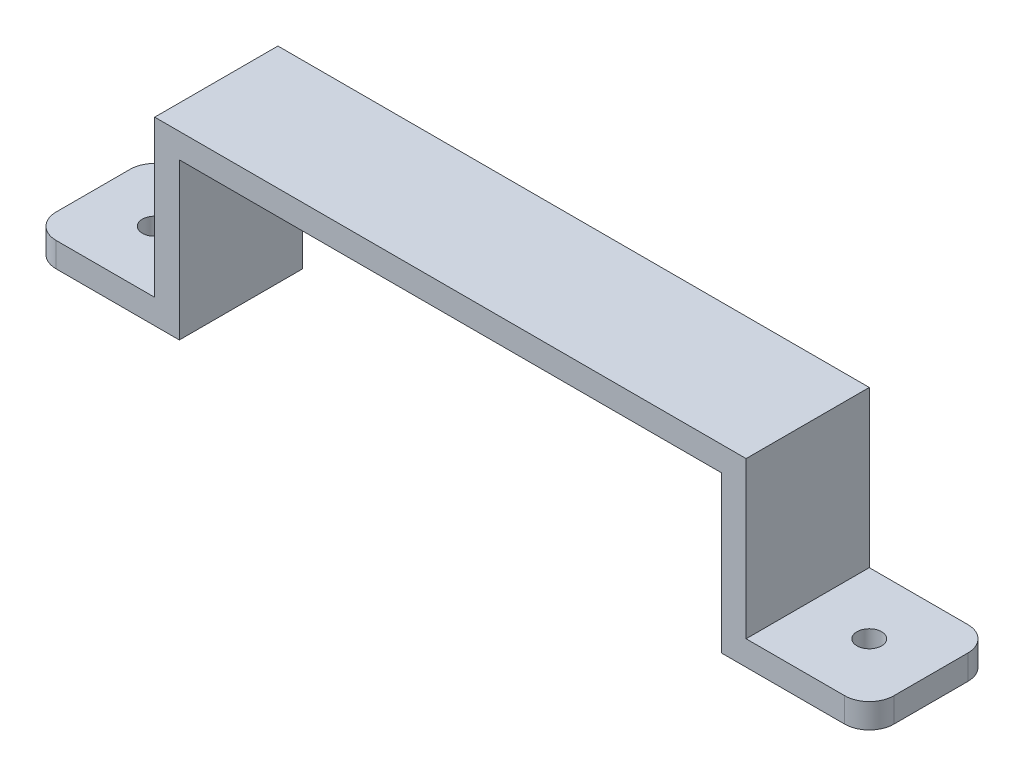
SolidWorks part; units mm, degrees
ref_plane "前视基准面" through (0, 0, 0) normal (0, 0, 1) x (1, 0, 0)
ref_plane "上视基准面" through (0, 0, 0) normal (0, 1, 0) x (1, 0, 0)
ref_plane "右视基准面" through (0, 0, 0) normal (1, 0, 0) x (0, 0, -1)
other "Configuration Table"
sketch "草图1" plane through (0, 0, 0) normal (0, 0, 1) x (1, 0, 0)
  line L0 (-36, 0) -> (36, 0)
  line L1 (36, 0) -> (36, -19)
  line L2 (36, -19) -> (51, -19)
  line L3 (51, -19) -> (51, -22)
  line L4 (51, -22) -> (33, -22)
  line L5 (33, -22) -> (33, -3)
  line L6 (33, -3) -> (-33, -3)
  line L7 (-33, -3) -> (-33, -22)
  line L8 (-33, -22) -> (-51, -22)
  line L9 (-51, -22) -> (-51, -19)
  line L10 (-51, -19) -> (-36, -19)
  line L11 (-36, -19) -> (-36, 0)
  line L12 (0, 0) -> (0, -25.8281) construction
  dimension "D1" = 3
  dimension "D2" = 3
  dimension "D3" = 3
  dimension "D4" = 66
  dimension "D5" = 19
  dimension "D6" = 15
extrude "凸台-拉伸1" add sketch "草图1" along normal blind 15
sketch "草图2" plane through (0, -19, 0) normal (0, 1, 0) x (1, 0, 0)
  line L0 (51, -15) -> (51, 0) construction
  line L1 (-51, -15) -> (-51, 0) construction
  line L2 (-36, 0) -> (-51, 0) construction
  line L3 (51, 0) -> (36, 0) construction
  circle A0 centre (-43.5, -7.5) radius 1.5
  circle A1 centre (43.5, -7.5) radius 1.5
  dimension "D3" = 3
  dimension "D1" = 7.5
  dimension "D2" = 7.5
  dimension "D4" = 7.5
  dimension "D5" = 7.5
extrude "切除-拉伸1" cut sketch "草图2" against normal blind 20
fillet "圆角1" radius 3 4 edges at (-51, -20.5, 15) (-51, -20.5, 0) (51, -20.5, 15) (51, -20.5, 0)
